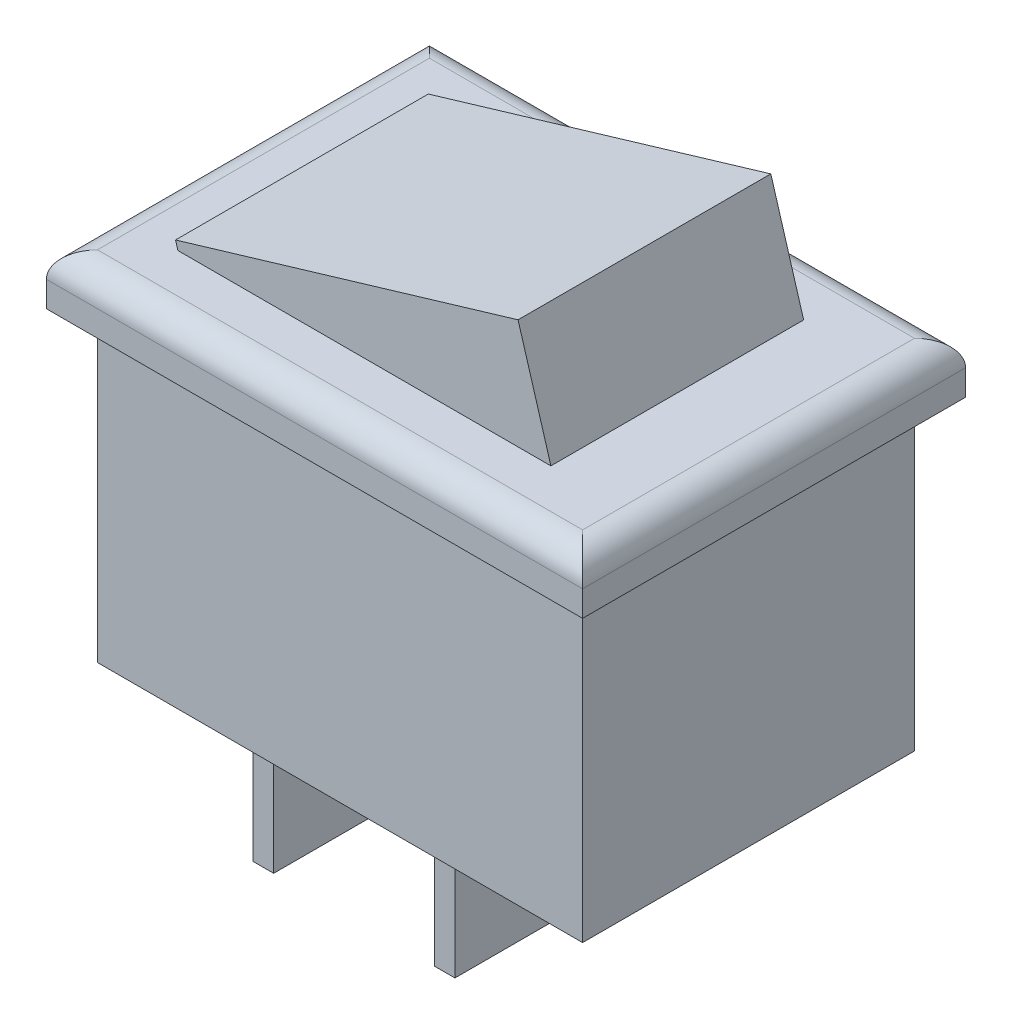
SolidWorks part; units mm, degrees
ref_plane "Plan de face" through (0, 0, 0) normal (0, 0, 1) x (1, 0, 0)
ref_plane "Plan de dessus" through (0, 0, 0) normal (0, 1, 0) x (1, 0, 0)
ref_plane "Plan de droite" through (0, 0, 0) normal (1, 0, 0) x (0, 0, -1)
sketch "Esquisse1" plane through (0, 0, 0) normal (0, 1, 0) x (1, 0, 0)
  line L1 (-10.5, -7.5) -> (10.5, -7.5)
  line L2 (-10.5, -7.5) -> (-10.5, 7.5)
  line L3 (-10.5, 7.5) -> (10.5, 7.5)
  line L4 (10.5, -7.5) -> (10.5, 7.5)
  line L5 (-10.5, -7.5) -> (10.5, 7.5) construction
  line L6 (-10.5, 7.5) -> (10.5, -7.5) construction
  point P0 (0, 0)
  dimension "D1" = 21
  dimension "D2" = 15
extrude "Boss.-Extru.1" add sketch "Esquisse1" along normal blind 2
sketch "Esquisse2" plane through (0, 2, 0) normal (0, 1, 0) x (1, 0, 0)
  line L1 (-9.5, -6.5) -> (9.5, -6.5)
  line L2 (-9.5, -6.5) -> (-9.5, 6.5)
  line L3 (-9.5, 6.5) -> (9.5, 6.5)
  line L4 (9.5, -6.5) -> (9.5, 6.5)
  line L5 (-9.5, -6.5) -> (9.5, 6.5) construction
  line L6 (-9.5, 6.5) -> (9.5, -6.5) construction
  point P0 (0, 0)
  dimension "D1" = 19
  dimension "D2" = 13
extrude "Boss.-Extru.2" add sketch "Esquisse2" against normal blind 14
sketch "Esquisse3" plane through (0, -12, 0) normal (0, -1, 0) x (1, 0, 0)
  line L1 (-7.5, 2.4) -> (-6.7, 2.4)
  line L2 (-7.5, 2.4) -> (-7.5, -2.4)
  line L3 (-7.5, -2.4) -> (-6.7, -2.4)
  line L4 (-6.7, 2.4) -> (-6.7, -2.4)
  line L5 (0.4, 2.4) -> (-0.4, 2.4)
  line L6 (0.4, 2.4) -> (0.4, -2.4)
  line L7 (0.4, -2.4) -> (-0.4, -2.4)
  line L8 (-0.4, 2.4) -> (-0.4, -2.4)
  point P8 (0.4, 0)
  point P12 (0, 2.4)
  dimension "D1" = 4.8
  dimension "D2" = 0.8
  dimension "D3" = 7.1
extrude "Boss.-Extru.3" add sketch "Esquisse3" along normal blind 7.8 separate body
fillet "Congé1" radius 1 4 edges at (0, 2, 7.5) (-10.5, 2, 0) (0, 2, -7.5) (10.5, 2, 0)
sketch "Esquisse4" plane through (0, 0, 0) normal (0, 0, 1) x (1, 0, 0)
  line L0 (-7.9939, 2.3124) -> (-6.7082, -2)
  line L1 (-7.9939, 2.3124) -> (5.4225, 6.3124)
  line L2 (-6.7082, -2) -> (6.7082, 2)
  line L3 (5.4225, 6.3124) -> (6.7082, 2)
  line L4 (-9.5, 2) -> (9.5, 2) construction
  dimension "D1" = 14
  dimension "D2" = 4.5
extrude "Boss.-Extru.4" add sketch "Esquisse4" along normal mid plane 9.9
